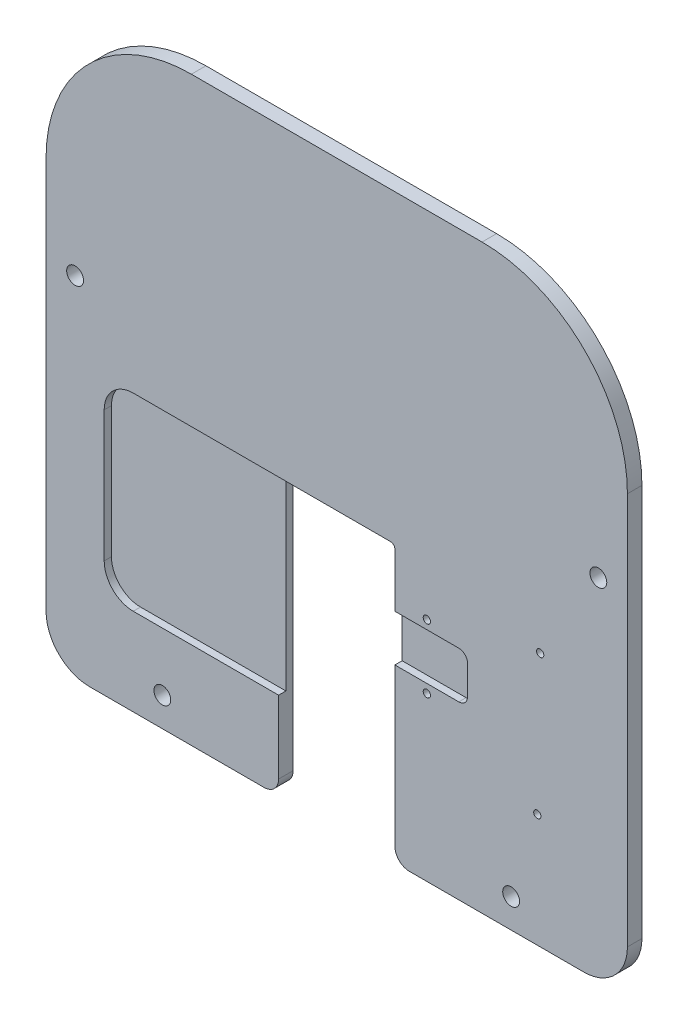
SolidWorks part; units mm, degrees
material "ｱｸﾘﾙ (中-上級の耐衝撃性)"
ref_plane "正面" through (0, 0, 0) normal (0, 0, 1) x (1, 0, 0)
ref_plane "平面" through (0, 0, 0) normal (0, 1, 0) x (1, 0, 0)
ref_plane "右側面" through (0, 0, 0) normal (1, 0, 0) x (0, 0, -1)
sketch "ｽｹｯﾁ1" plane through (0, 0, 0) normal (0, 0, 1) x (1, 0, 0)
  line L1 (-100, 110) -> (100, 110)
  line L2 (-100, 110) -> (-100, -90)
  line L3 (-100, -90) -> (100, -90)
  line L4 (100, 110) -> (100, -90)
  dimension "D1" = 200
  dimension "D2" = 90
  dimension "D3" = 100
  dimension "D4" = 200
extrude "ﾎﾞｽ - 押し出し1" add sketch "ｽｹｯﾁ1" along normal blind 5
sketch "ｽｹｯﾁ2" plane through (0, 0, 5) normal (0, 0, 1) x (1, 0, 0)
  line L0 (-100, -90) -> (100, -90) construction
  line L1 (-20, 5) -> (20, 5)
  line L2 (-20, 5) -> (-20, -90)
  line L3 (-20, -90) -> (20, -90)
  line L4 (20, 5) -> (20, -90)
  line L5 (-100, 110) -> (-100, -90) construction
  dimension "D1" = 40
  dimension "D2" = 80
  dimension "D3" = 95
extrude "ｶｯﾄ - 押し出し1" cut sketch "ｽｹｯﾁ2" against normal through all
fillet "ﾌｨﾚｯﾄ1" radius 50 2 edges at (100, 110, 2.5) (-100, 110, 2.5)
fillet "ﾌｨﾚｯﾄ2" radius 1.5 1 edges at (20, 5, 2.5)
sketch "ｽｹｯﾁ3" plane through (0, 0, 5) normal (0, 0, 1) x (1, 0, 0)
  circle A0 centre (31, -34) radius 1.6 construction
  circle A1 centre (70, -2.5) radius 1.6 construction
  circle A2 centre (31, -12) radius 1.6 construction
  circle A3 centre (69, -51) radius 1.6 construction
  circle A4 centre (31, -34) radius 1.6
  circle A5 centre (70, -2.5) radius 1.6
  circle A6 centre (31, -12) radius 1.6
  circle A7 centre (69, -51) radius 1.6
hole_wizard "M3x0.5 ねじ穴用ねじ下穴ﾄﾞﾘﾙ1" positions "ｽｹｯﾁ6" profile "ｽｹｯﾁ5" hole size "M3x0.5" standard "ANSIﾒｰﾄﾙ"
sketch "ｽｹｯﾁ6" plane through (0, 0, 5) normal (0, 0, 1) x (1, 0, 0)
  point P1 (70, -2.5)
  point P4 (31, -12)
  point P7 (31, -34)
  point P10 (69, -51)
sketch "ｽｹｯﾁ5" plane through (70, -2.5, 5) normal (1, 0, 0) x (0, -1, 0)
  line L0 (0, 0) -> (0, 5.7511)
  line L1 (0, 5.7511) -> (1.25, 5)
  line L2 (1.25, 5) -> (1.25, 0)
  line L5 (1.25, 0) -> (0, 0)
  line L10 (0, 5.7511) -> (-1.25, 5) construction
  line L11 (0, -6.35) -> (0, 107.95) construction
  dimension "穴の直径" = 2.5
  dimension "穴の深さ" = 5
  dimension "ﾄﾞﾘﾙ角度" = 118
fillet "ﾌｨﾚｯﾄ3" radius 15 2 edges at (-100, -90, 2.5) (100, -90, 2.5)
fillet "ﾌｨﾚｯﾄ4" radius 5 2 edges at (-20, -90, 2.5) (20, -90, 2.5)
hole_wizard "M5 すきま穴1" positions "ｽｹｯﾁ8" profile "ｽｹｯﾁ7" hole size "M5" standard "ANSIﾒｰﾄﾙ"
sketch "ｽｹｯﾁ8" plane through (0, 0, 0) normal (0, 0, -1) x (-1, 0, 0)
  line L0 (-25, -90) -> (-85, -90) construction
  line L1 (85, -90) -> (25, -90) construction
  line L2 (-100, -75) -> (-100, 60) construction
  line L3 (100, 60) -> (100, -75) construction
  point P0 (-60, -80)
  point P1 (60, -80)
  point P3 (-90, 30)
  point P5 (90, 30)
  dimension "D1" = 10
  dimension "D2" = 10
  dimension "D3" = 40
  dimension "D4" = 40
  dimension "D5" = 10
  dimension "D6" = 10
  dimension "D7" = 120
  dimension "D8" = 120
sketch "ｽｹｯﾁ7" plane through (60, -80, 0) normal (1, 0, 0) x (0, 1, 0)
  line L0 (0, 0) -> (0, 6.7425)
  line L1 (0, 6.7425) -> (2.9, 5)
  line L2 (2.9, 5) -> (2.9, 0)
  line L5 (2.9, 0) -> (0, 0)
  line L10 (0, 6.7425) -> (-2.9, 5) construction
  line L11 (0, -6.35) -> (0, 107.95) construction
  dimension "穴の直径" = 5.8
  dimension "穴の深さ" = 5
  dimension "ﾄﾞﾘﾙ角度" = 118
sketch "ｽｹｯﾁ10" plane through (0, 0, 5) normal (0, 0, 1) x (1, 0, 0)
  line L0 (-20, 5) -> (-20, -85) construction
  line L1 (-80, 5) -> (-20, 5)
  line L2 (-80, 5) -> (-80, -60)
  line L3 (-80, -60) -> (-20, -60)
  line L4 (-20, 5) -> (-20, -60)
  line L5 (-85, -90) -> (-25, -90) construction
  line L6 (-100, 60) -> (-100, -75) construction
  dimension "D1" = 30
  dimension "D2" = 20
  dimension "D3" = 65
extrude "ｶｯﾄ - 押し出し2" cut sketch "ｽｹｯﾁ10" against normal blind 2.5
fillet "ﾌｨﾚｯﾄ5" radius 10 2 edges at (-80, -60, 3.75) (-80, 5, 3.75)
sketch "ｽｹｯﾁ11" plane through (0, 0, 5) normal (0, 0, 1) x (1, 0, 0)
  line L0 (20, -85) -> (20, 3.5) construction
  line L1 (20, -15) -> (45, -15)
  line L2 (20, -15) -> (20, -31)
  line L3 (20, -31) -> (45, -31)
  line L4 (45, -15) -> (45, -31)
  circle A0 centre (31, -12) radius 1.25 construction
  circle A1 centre (31, -34) radius 1.25 construction
  dimension "D1" = 3
  dimension "D2" = 3
  dimension "D3" = 25
extrude "ｶｯﾄ - 押し出し3" cut sketch "ｽｹｯﾁ11" against normal blind 2.5
fillet "ﾌｨﾚｯﾄ6" radius 3 2 edges at (45, -31, 3.75) (45, -15, 3.75)
